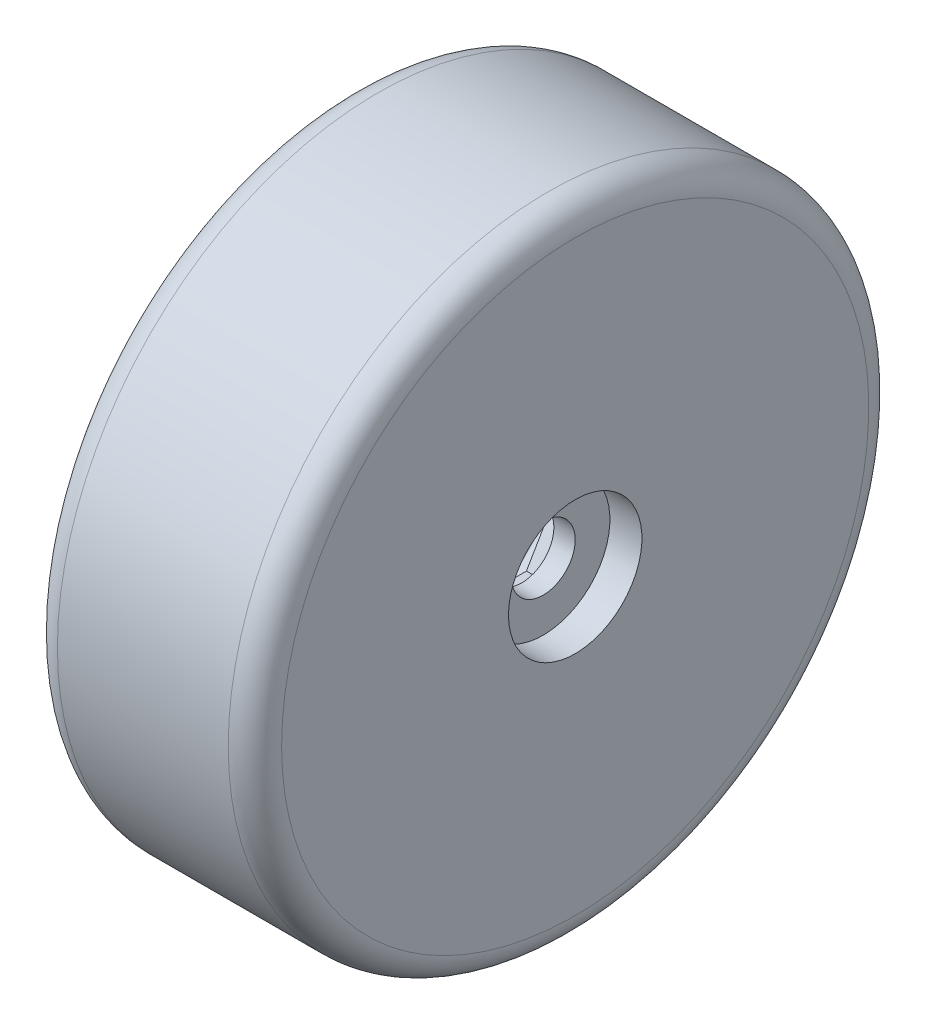
SolidWorks part; units mm, degrees
ref_plane "Front Plane" through (0, 0, 0) normal (0, 0, 1) x (1, 0, 0)
ref_plane "Top Plane" through (0, 0, 0) normal (0, 1, 0) x (1, 0, 0)
ref_plane "Right Plane" through (0, 0, 0) normal (1, 0, 0) x (0, 0, -1)
sketch "Sketch1" plane through (0, 0, 0) normal (0, 0, 1) x (1, 0, 0)
  line L0 (-33.6279, 0) -> (48.8372, 0) construction
  line L1 (0, -6) -> (0, -55)
  line L2 (-5, -60) -> (-37, -60)
  line L3 (-42, -55) -> (-42, -45)
  line L4 (-37, -40) -> (-19, -40)
  line L5 (-14, -35) -> (-14, -6)
  line L6 (-14, -6) -> (0, -6)
  arc A0 (-37, -40) -> (-42, -45) centre (-37, -45) ccw
  arc A1 (-14, -35) -> (-19, -40) centre (-19, -35) cw
  arc A2 (0, -55) -> (-5, -60) centre (-5, -55) cw
  arc A3 (-42, -55) -> (-37, -60) centre (-37, -55) ccw
  point P5 (-7, -6)
  dimension "D6" = 5
  dimension "D1" = 6
  dimension "D2" = 60
  dimension "D3" = 20
  dimension "D4" = 42
  dimension "D5" = 14
revolve "Revolve1" add sketch "Sketch1" angle 360 about L0
sketch "Sketch2" plane through (-14, 0, 0) normal (-1, 0, 0) x (0, 0, 1)
  line L1 (4.948, -8.4765) -> (9.8148, 0.0469)
  line L2 (9.8148, 0.0469) -> (4.8668, 8.5233)
  line L3 (4.8668, 8.5233) -> (-4.948, 8.4765)
  line L4 (-4.948, 8.4765) -> (-9.8148, -0.0469)
  line L5 (-9.8148, -0.0469) -> (-4.8668, -8.5233)
  line L6 (-4.8668, -8.5233) -> (4.948, -8.4765)
  circle A0 centre (0, 0) radius 8.5 construction
  dimension "D1" = 17
extrude "Cut-Extrude1" cut sketch "Sketch2" against normal blind 4 contours L3 L4 L5 L6 L1 L2
sketch "Sketch3" plane through (0, 0, 0) normal (0, 0, 1) x (1, 0, 0)
  line L0 (0, 0) -> (0, -12.5)
  line L1 (0, -55) -> (0, 55) construction
  line L2 (0, -12.5) -> (-6, -12.5)
  line L3 (-6, -12.5) -> (-6, 0)
  line L4 (-6, 0) -> (0, 0)
  line L5 (-10, 6) -> (-10, -6) construction
  dimension "D1" = 4
  dimension "D2" = 12.5
revolve "Cut-Revolve1" cut sketch "Sketch3" angle 360 about L4
